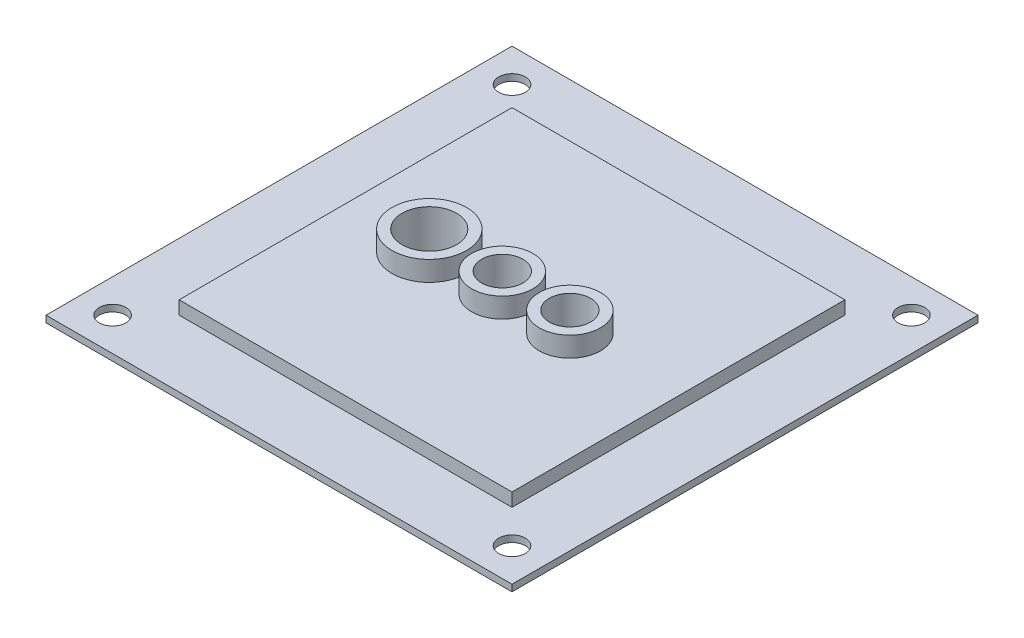
SolidWorks part; units mm, degrees
ref_plane "Front Plane" through (0, 0, 0) normal (0, 0, 1) x (1, 0, 0)
ref_plane "Top Plane" through (0, 0, 0) normal (0, 1, 0) x (1, 0, 0)
ref_plane "Right Plane" through (0, 0, 0) normal (1, 0, 0) x (0, 0, -1)
sketch "Sketch1" plane through (0, 0, 0) normal (0, 1, 0) x (1, 0, 0)
  line L0 (-25, 25) -> (25, 25) construction
  line L1 (25, 0) -> (-25, 0)
  line L2 (25, 0) -> (25, 50)
  line L3 (25, 50) -> (-25, 50)
  line L4 (-25, 0) -> (-25, 50)
  circle A0 centre (-12.4266, 25) radius 4.1
  circle A4 centre (-1.4608, 25) radius 3.1
  circle A23 centre (8.6987, 25) radius 3.1
  point P0 (0, 0)
  point P8 (-16.764, 18.5653)
  point P9 (-17.1026, 25)
  point P10 (-3.6237, 25)
  point P11 (-4.9107, 16.1269)
  point P12 (0, 0)
  point P13 (0, 0)
  point P14 (-4.7752, 25)
  point P17 (4.7075, 25)
  point P18 (8.6987, 25)
  point P21 (-1.4608, 25)
  point P22 (-12.4266, 25)
  dimension "D3" = 8.2
  dimension "D6" = 6.2
  dimension "D1" = 50
  dimension "D2" = 50
extrude "Boss-Extrude1" add sketch "Sketch1" along normal mid plane 3
sketch "Sketch2" plane through (0, 1.5, 0) normal (0, 1, 0) x (1, 0, 0)
  circle A0 centre (8.6987, 25) radius 3.1 construction
  circle A1 centre (-12.4266, 25) radius 4.1
  circle A2 centre (-12.4266, 25) radius 4.1
  circle A3 centre (8.6987, 25) radius 3.1
  circle A11 centre (-1.4608, 25) radius 3.1
  circle A12 centre (-1.4608, 25) radius 3.1
  dimension "D1" = 0
  dimension "D6" = 0
extrude "Extrude-Thin1" add sketch "Sketch2" along normal blind 3 thin
sketch "Sketch3" plane through (0, -1.5, 0) normal (0, -1, 0) x (1, 0, 0)
  line L0 (-35, 10) -> (-35, -60)
  line L1 (-35, -60) -> (35, -60)
  line L2 (35, -60) -> (35, 10)
  line L3 (35, 10) -> (-35, 10)
  line L4 (-25, 0) -> (-25, -50)
  line L5 (-25, -50) -> (25, -50)
  line L6 (25, -50) -> (25, 0)
  line L7 (25, 0) -> (-25, 0)
  line L8 (-25, 0) -> (-25, -50)
  line L9 (-25, -50) -> (25, -50)
  line L10 (25, -50) -> (25, 0)
  line L11 (25, 0) -> (-25, 0)
  line L12 (30, 5) -> (-30, 5) construction
  line L13 (-30, 5) -> (-30, -55) construction
  line L14 (-30, -55) -> (30, -55) construction
  line L15 (30, -55) -> (30, 5) construction
  circle A0 centre (-30, 5) radius 2
  circle A1 centre (30, 5) radius 2
  circle A2 centre (30, -55) radius 2
  circle A3 centre (-30, -55) radius 2
  dimension "D4" = 4
  dimension "D1" = 0
  dimension "D2" = 10
  dimension "D3" = 5
extrude "Boss-Extrude2" add sketch "Sketch3" against normal blind 1
